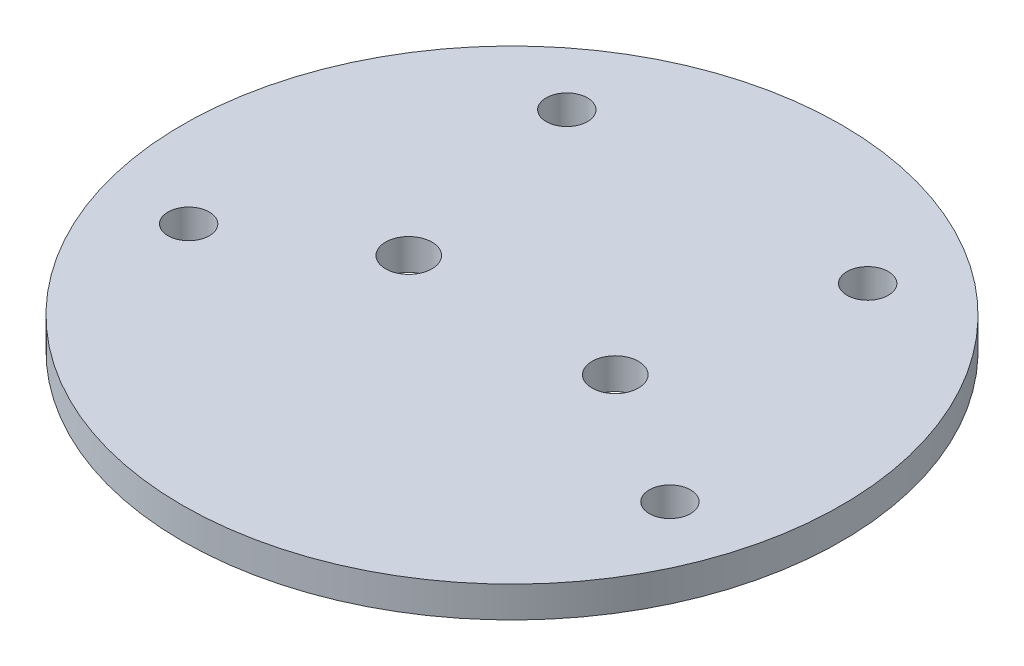
SolidWorks part; units mm, degrees
material "5052-H32"
ref_plane "Front Plane" through (0, 0, 0) normal (0, 0, 1) x (1, 0, 0)
ref_plane "Top Plane" through (0, 0, 0) normal (0, 1, 0) x (1, 0, 0)
ref_plane "Right Plane" through (0, 0, 0) normal (1, 0, 0) x (0, 0, -1)
sketch "Sketch1" plane through (0, 0, 0) normal (0, 1, 0) x (1, 0, 0)
  line L0 (0, 0) -> (-23.1297, 31.5565) construction
  line L1 (0, 0) -> (-41.7254, 0) construction
  line L2 (-37.0005, -12.7186) -> (0, 0) construction
  line L3 (0, -31.6103) -> (0, 47.1695) construction
  circle A0 centre (0, 0) radius 50.673
  circle A3 centre (-15.875, 0) radius 3.5687
  circle A4 centre (15.875, 0) radius 3.5687
  circle A5 centre (-37.0005, -12.7186) radius 3.175
  circle A8 centre (-23.1297, 31.5565) radius 3.175
  circle A9 centre (23.1297, 31.5565) radius 3.175
  circle A10 centre (37.0005, -12.7186) radius 3.175
  dimension "D1" = 101.346
  dimension "D2" = 6.35
  dimension "D3" = 6.35
  dimension "D5" = 15.875
  dimension "D6" = 15.875
  dimension "D4" = 39.1254
  dimension "D7" = 53.76
  dimension "D8" = 39.1254
  dimension "D9" = 18.97
extrude "Boss-Extrude1" add sketch "Sketch1" along normal blind 4.7752
equation "\"allrockets_tube_ID\"= 3.85in"
equation "\"allrockets_tube_OD\"= 4.024in"
equation "\"hole\"= 6.35mm"
equation "\"back_plate_width\"= 28mm"
equation "\"card_spacing\"= 20mm"
equation "\"card_number\"= 6"
equation "\"ToDi\"= 0.05mm"
equation "\"card_diameter\"= 85.86mm"
equation "\"overlap\"= 6.6mm"
equation "\"card_length\"= 68mm"
equation "\"rack_hole_tol\"= 0.35mm"
equation "\"rack_front_width\"= 11.63mm"
equation "\"hole_b_d\"= 39.12541885mm"
equation "\"hole_b_a\"= 18.9721389deg"
equation "\"hole_u_d\"= 39.12541885mm"
equation "\"hole_u_a\"= 53.76090642deg"
equation "\"card_h\"= 61.73mm"
equation "\"sphinx_av\"= 50.292mm"
equation "\"tb_spacing\"= 25mm"
equation "\"D2@Sketch1\"=\"hole\""
equation "\"D4@Sketch1\"=\"hole_u_d\""
equation "\"D7@Sketch1\"=\"hole_u_a\""
equation "\"D8@Sketch1\"=\"hole_b_d\""
equation "\"D9@Sketch1\"=\"hole_b_a\""
